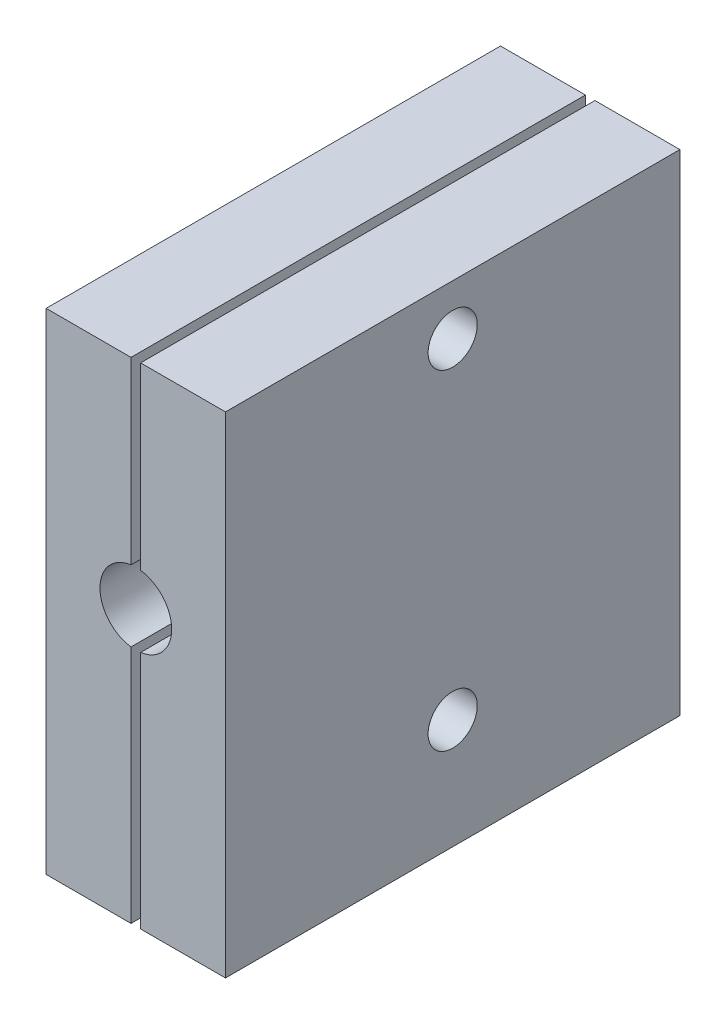
SolidWorks part; units mm, degrees
ref_plane "Front Plane" through (0, 0, 0) normal (0, 0, 1) x (1, 0, 0)
ref_plane "Top Plane" through (0, 0, 0) normal (0, 1, 0) x (1, 0, 0)
ref_plane "Right Plane" through (0, 0, 0) normal (1, 0, 0) x (0, 0, -1)
sketch "Sketch1" plane through (0, 0, 0) normal (0, 0, 1) x (1, 0, 0)
  line L0 (0, -13.4937) -> (0, 21.4313) construction
  line L1 (-11.9063, -32.5437) -> (11.9063, -32.5437)
  line L2 (-11.9063, -32.5437) -> (-11.9062, 32.5438)
  line L3 (-11.9062, 32.5438) -> (11.9063, 32.5438)
  line L4 (11.9063, -32.5437) -> (11.9063, 32.5438)
  line L5 (-11.9063, -32.5437) -> (11.9063, 32.5438) construction
  line L6 (-11.9062, 32.5438) -> (11.9063, -32.5437) construction
  line L7 (0, -32.5437) -> (0, -13.4937) construction
  circle A1 centre (0, -13.4937) radius 0.4699
  circle A2 centre (0, 21.4313) radius 0.4699
  circle A3 centre (0, 3.9688) radius 4.7625
  point P0 (0, 0)
  dimension "D3" = 9.525
  dimension "D4" = 34.925
  dimension "D5" = 0.9398
  dimension "D6" = 19.05
  dimension "D1" = 23.8125
  dimension "D2" = 65.0875
extrude "Boss-Extrude1" add sketch "Sketch1" along normal mid plane 60.325
hole_wizard "1/4 Clearance Hole1" positions "Sketch3" profile "Sketch2" hole size "1/4" standard "ANSI Inch" end condition through all
sketch "Sketch3" plane through (-11.9062, 0, 0) normal (-1, 0, 0) x (0, 0, 1)
  line L0 (0, 21.4313) -> (0, -13.4937) construction
  line L2 (30.1625, 21.4313) -> (0, 21.4313) construction
  line L4 (0, -13.4937) -> (30.1625, -13.4937) construction
  line L5 (30.1625, 20.9614) -> (30.1625, 21.9012) construction
  line L6 (30.1625, -13.9636) -> (30.1625, -13.0238) construction
  line L7 (0, 21.4313) -> (0, 25.8763) construction
  line L8 (0, -13.4937) -> (0, -17.9387) construction
  point P0 (0, 25.8763)
  point P2 (0, -17.9387)
  dimension "D1" = 4.445
sketch "Sketch2" plane through (-11.9062, 25.8763, 0) normal (0, 1, 0) x (0, 0, 1)
  line L0 (0, 0) -> (0, 23.8125)
  line L1 (0, 23.8125) -> (3.2639, 23.8125)
  line L2 (3.2639, 23.8125) -> (3.2639, 0)
  line L5 (3.2639, 0) -> (0, 0)
  line L11 (0, -6.35) -> (0, 107.95) construction
  dimension "Thru Hole Dia." = 6.5278
  dimension "Thru Hole Depth" = 23.8125
sketch "Sketch4" plane through (0, 0, 0) normal (0, 0, 1) x (1, 0, 0)
  line L0 (11.9063, 32.5438) -> (-11.9062, 32.5438) construction
  line L1 (-0.635, -32.5438) -> (0.635, -32.5438)
  line L2 (-0.635, -32.5438) -> (-0.635, 32.5438)
  line L3 (-0.635, 32.5438) -> (0.635, 32.5438)
  line L4 (0.635, -32.5438) -> (0.635, 32.5438)
  line L5 (-0.635, -32.5438) -> (0.635, 32.5438) construction
  line L6 (-0.635, 32.5438) -> (0.635, -32.5438) construction
  point P0 (0, 0)
  dimension "D1" = 1.27
extrude "Cut-Extrude1" cut sketch "Sketch4" against normal through all both and the other way through all
